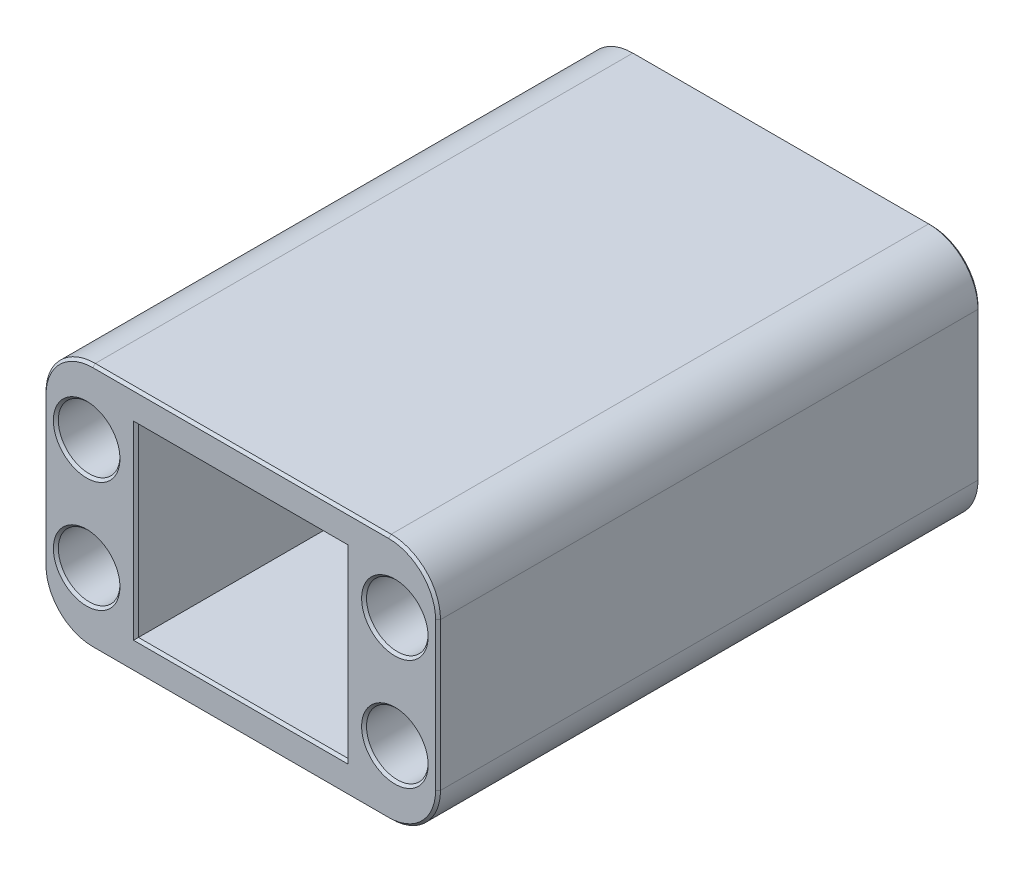
SolidWorks part; units mm, degrees
ref_plane "Front Plane" through (0, 0, 0) normal (0, 0, 1) x (1, 0, 0)
ref_plane "Top Plane" through (0, 0, 0) normal (0, 1, 0) x (1, 0, 0)
ref_plane "Right Plane" through (0, 0, 0) normal (1, 0, 0) x (0, 0, -1)
sketch "Sketch1" plane through (0, 0, 0) normal (0, 0, 1) x (1, 0, 0)
  line L0 (-15.875, 5.715) -> (15.875, 5.715) construction
  line L1 (15.875, 5.715) -> (15.875, -5.715) construction
  line L2 (15.875, -5.715) -> (-15.875, -5.715) construction
  line L3 (-15.875, -5.715) -> (-15.875, 5.715) construction
  line L4 (-15.875, 5.715) -> (15.875, -5.715) construction
  line L5 (15.875, 5.715) -> (-15.875, -5.715) construction
  line L7 (-20.32, -12.7) -> (20.32, -12.7)
  line L8 (-20.32, -12.7) -> (-20.32, 12.7)
  line L9 (-20.32, 12.7) -> (20.32, 12.7)
  line L10 (20.32, -12.7) -> (20.32, 12.7)
  line L11 (-20.32, -12.7) -> (20.32, 12.7) construction
  line L12 (-20.32, 12.7) -> (20.32, -12.7) construction
  line L13 (-10.795, -9.525) -> (10.795, -9.525)
  line L14 (-10.795, -9.525) -> (-10.795, 9.525)
  line L15 (-10.795, 9.525) -> (10.795, 9.525)
  line L16 (10.795, -9.525) -> (10.795, 9.525)
  line L17 (-10.795, -9.525) -> (10.795, 9.525) construction
  line L18 (-10.795, 9.525) -> (10.795, -9.525) construction
  circle A0 centre (-15.875, 5.715) radius 3.175
  circle A1 centre (15.875, 5.715) radius 3.175
  circle A2 centre (15.875, -5.715) radius 3.175
  circle A3 centre (-15.875, -5.715) radius 3.175
  point P2 (0, 0)
  point P10 (0, 0)
  point P15 (-15.875, 0)
  point P16 (-20.32, 0)
  point P17 (0, 5.715)
  point P18 (0, 12.7)
  point P19 (0, 0)
  dimension "D3" = 6.35
  dimension "D1" = 31.75
  dimension "D2" = 11.43
  dimension "D4" = 25.4
  dimension "D5" = 40.64
  dimension "D6" = 21.59
  dimension "D7" = 19.05
extrude "Boss-Extrude1" add sketch "Sketch1" along normal blind 55.88
fillet "Fillet1" radius 5.08 4 edges at (-20.32, -12.7, 27.94) (20.32, -12.7, 27.94) (20.32, 12.7, 27.94) (-20.32, 12.7, 27.94)
chamfer "Chamfer1" distance 0.254 angle 45 32 edges at (-10.795, 0, 0) (0, 9.525, 0) (10.795, 0, 0) (0, -9.525, 0) (-12.7, -5.715, 0) (19.05, 5.715, 0) (18.8321, -11.2121, 0) (20.32, 0, 0) (18.8321, 11.2121, 0) (0, 12.7, 0) (-18.8321, 11.2121, 0) (-20.32, 0, 0) (-18.8321, -11.2121, 0) (0, -12.7, 0) (-12.7, 5.715, 0) (19.05, -5.715, 0) (0, 9.525, 55.88) (-10.795, 0, 55.88) (0, -9.525, 55.88) (10.795, 0, 55.88) (-18.8321, 11.2121, 55.88) (0, 12.7, 55.88) (18.8321, 11.2121, 55.88) (20.32, 0, 55.88) (18.8321, -11.2121, 55.88) (0, -12.7, 55.88) (-18.8321, -11.2121, 55.88) (-20.32, 0, 55.88) (-12.7, 5.715, 55.88) (19.05, 5.715, 55.88) (19.05, -5.715, 55.88) (-12.7, -5.715, 55.88)
